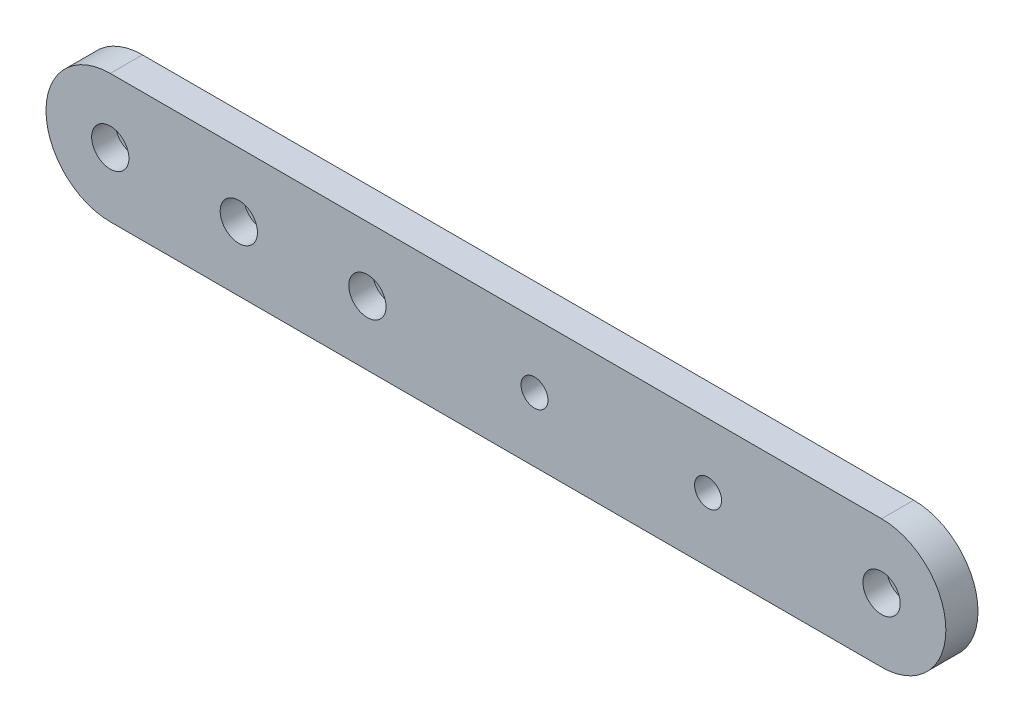
SolidWorks part; units mm, degrees
material "Alliage 1060"
ref_plane "Plan de face" through (0, 0, 0) normal (0, 0, 1) x (1, 0, 0)
ref_plane "Plan de dessus" through (0, 0, 0) normal (0, 1, 0) x (1, 0, 0)
ref_plane "Plan de droite" through (0, 0, 0) normal (1, 0, 0) x (0, 0, -1)
sketch "Esquisse1" plane through (0, 0, 0) normal (0, 0, 1) x (1, 0, 0)
  line L0 (-106.2301, 0) -> (98.7434, 0) construction
  line L1 (-60, 10) -> (60, 10)
  line L2 (0, 59.3877) -> (0, -51.0916) construction
  line L3 (60, -10) -> (-60, -10)
  arc A0 (60, -10) -> (60, 10) centre (60, 0) ccw
  arc A1 (-60, -10) -> (-60, 10) centre (-60, 0) cw
  circle A2 centre (-40, 0) radius 1.5
  circle A3 centre (-20, 0) radius 1.5
  circle A4 centre (-60, 0) radius 1.5
  circle A5 centre (60, 0) radius 1.5
  dimension "D3" = 20
  dimension "D1" = 80
  dimension "D4" = 3
  dimension "D5" = 100
  dimension "D2" = 120
extrude "Extrusion1" add sketch "Esquisse1" along normal blind 5
sketch "Esquisse2" plane through (0, 0, 1.3) normal (0, 0, -1) x (-1, 0, 0)
  circle A0 centre (-60, 0) radius 2.9
  circle A1 centre (60, 0) radius 2.9
  circle A2 centre (-60, 0) radius 2.9 construction
  circle A4 centre (20, 0) radius 2.9
  circle A5 centre (40, 0) radius 2.9
  circle A6 centre (40, 0) radius 1.5 construction
  circle A7 centre (20, 0) radius 1.5 construction
  circle A8 centre (60, 0) radius 1.5 construction
extrude "Enlèv. mat.-Extru.1" cut sketch "Esquisse2" against normal through all
sketch "Esquisse3" plane through (0, 0, 0) normal (0, 0, -1) x (-1, 0, 0)
  circle A0 centre (-6, 0) radius 2.1
  circle A1 centre (-33, 0) radius 2.1
  circle A2 centre (-6, 0) radius 1.65 construction
  circle A3 centre (-33, 0) radius 1.65 construction
  dimension "D1" = 4.2
extrude "Enlèv. mat.-Extru.2" cut sketch "Esquisse3" against normal through all
